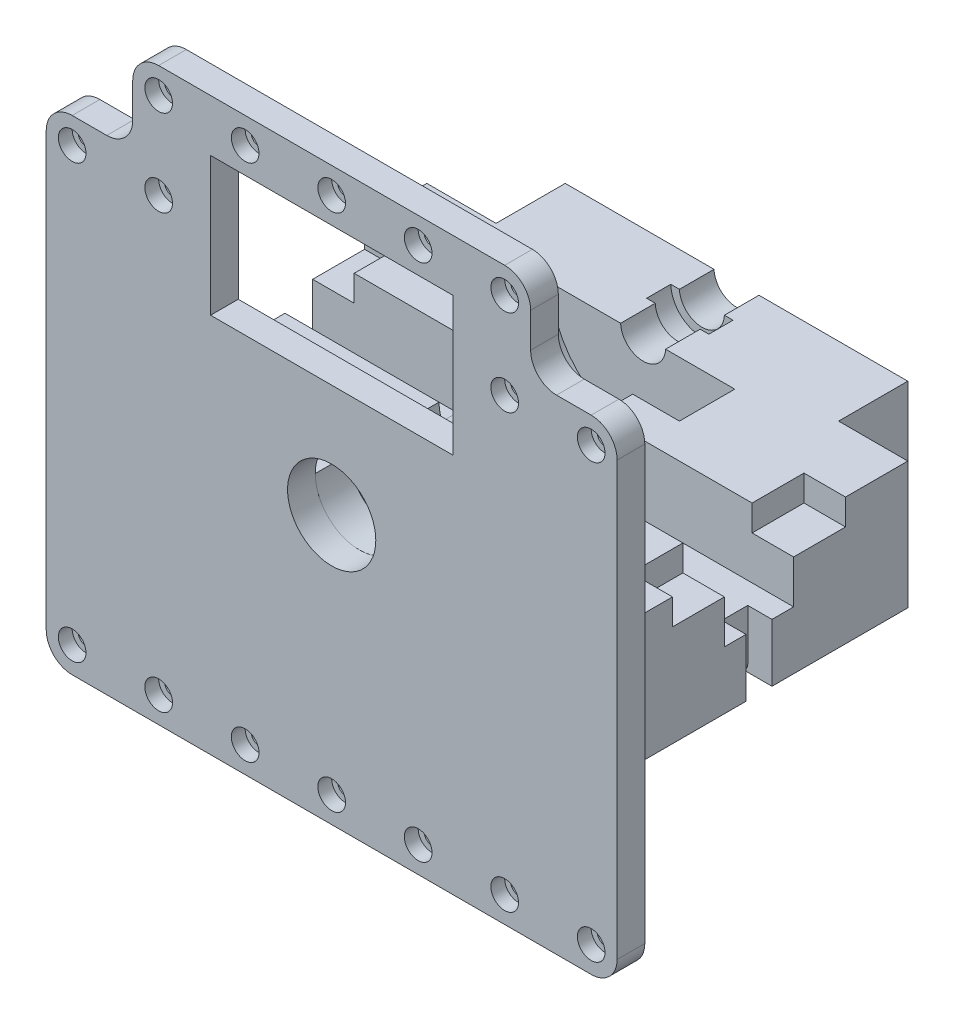
SolidWorks part; units mm, degrees
ref_plane "Front Plane" through (0, 0, 0) normal (0, 0, 1) x (1, 0, 0)
ref_plane "Top Plane" through (0, 0, 0) normal (0, 1, 0) x (1, 0, 0)
ref_plane "Right Plane" through (0, 0, 0) normal (1, 0, 0) x (0, 0, -1)
sketch "Sketch2" plane through (0, 0, 0) normal (0, 0, 1) x (1, 0, 0)
  line L5 (-57.5, 60) -> (-57.5, 50)
  line L6 (-75, -97.5) -> (75, -97.5)
  line L24 (-82.5, -90) -> (-82.5, 35)
  line L25 (-50, 67.5) -> (50, 67.5)
  line L26 (82.5, -90) -> (82.5, 35)
  line L27 (0, -100) -> (0, 100) construction
  line L28 (-100, 0) -> (100, 0) construction
  line L29 (-65, 42.5) -> (-75, 42.5)
  line L34 (57.5, 60) -> (57.5, 50)
  line L35 (65, 42.5) -> (75, 42.5)
  arc A12 (-82.5, 35) -> (-75, 42.5) centre (-75, 35) cw
  arc A19 (82.5, 35) -> (75, 42.5) centre (75, 35) ccw
  arc A20 (65, 42.5) -> (57.5, 50) centre (65, 50) cw
  arc A21 (57.5, 60) -> (50, 67.5) centre (50, 60) ccw
  arc A22 (-50, 67.5) -> (-57.5, 60) centre (-50, 60) ccw
  arc A23 (-65, 42.5) -> (-57.5, 50) centre (-65, 50) ccw
  arc A24 (-82.5, -90) -> (-75, -97.5) centre (-75, -90) ccw
  arc A25 (82.5, -90) -> (75, -97.5) centre (75, -90) cw
  point P0 (0, 0)
  point P39 (-57.5, 67.5)
  dimension "D5" = 25
  dimension "D6" = 82.5
  dimension "D7" = 7.5
  dimension "D2" = 25
  dimension "D3" = 165
  dimension "D8" = 7.5
  dimension "D1" = 67.5
  dimension "D4" = 82.5
extrude "Boss-Extrude1" add sketch "Sketch2" against normal blind 8
sketch "Sketch3" plane through (0, 0, 0) normal (0, 0, 1) x (1, 0, 0)
  line L0 (0, 100) -> (0, -100) construction
  circle A0 centre (0, -20) radius 12.75
  dimension "D1" = 25.5
  dimension "D2" = 20
extrude "Cut-Extrude1" cut sketch "Sketch3" against normal up to surface (8 mm away) up to face at (0, 13.75, -8)
sketch "Sketch5" plane through (0, 0, -8) normal (0, 0, -1) x (-1, 0, 0)
  line L3 (-69.5, -87) -> (-69.5, -20)
  line L4 (0, 67.5) -> (0, -97.5) construction
  line L5 (-82.5, -90) -> (-82.5, 35) construction
  line L6 (-69.5, -20) -> (69.5, -20)
  line L7 (-69.5, -87) -> (69.5, -87)
  line L8 (75, -97.5) -> (-75, -97.5) construction
  line L9 (69.5, -87) -> (69.5, -20)
  line L10 (-50, 67.5) -> (50, 67.5) construction
  point P10 (0, -87)
  point P11 (0, -20)
  dimension "D1" = 10.5
  dimension "D2" = 67
  dimension "D3" = 13
extrude "Boss-Extrude2" add sketch "Sketch5" along normal blind 109
sketch "Sketch6" plane through (0, 0, -8) normal (0, 0, -1) x (-1, 0, 0)
  circle A0 centre (0, -20) radius 26.5
  circle A1 centre (0, -20) radius 12.75 construction
  dimension "D1" = 53
extrude "Cut-Extrude2" cut sketch "Sketch6" along normal blind 16 from offset 10
sketch "Sketch7" plane through (0, 0, -8) normal (0, 0, -1) x (-1, 0, 0)
  circle A0 centre (0, -20) radius 6.5
  circle A1 centre (0, -20) radius 12.75 construction
  dimension "D1" = 13
extrude "Cut-Extrude3" cut sketch "Sketch7" along normal up to surface (109 mm away) up to face at (0, -53.5, -117)
sketch "Sketch10" plane through (0, 0, -8) normal (0, 0, -1) x (-1, 0, 0)
  line L0 (-69.5, -20) -> (-69.5, -20.25)
  line L1 (-69.5, -20) -> (-69.5, -87) construction
  line L2 (-69.5, -20.25) -> (69.5, -20.25)
  line L3 (69.5, -87) -> (69.5, -20) construction
  line L4 (69.5, -20.25) -> (69.5, -20)
  line L5 (69.5, -20) -> (-69.5, -20)
  dimension "D1" = 0.25
extrude "Cut-Extrude4" cut sketch "Sketch10" along normal up to surface (109 mm away) up to face at (0, -43.4167, -117)
sketch "Sketch11" plane through (0, 0, -8) normal (0, 0, -1) x (-1, 0, 0)
  line L0 (-69.5, -72) -> (-54.5, -72)
  line L1 (-69.5, -20.25) -> (-69.5, -87) construction
  line L2 (-54.5, -72) -> (-54.5, -87)
  line L3 (-69.5, -87) -> (69.5, -87) construction
  line L4 (-69.5, -72) -> (-69.5, -87)
  line L5 (-69.5, -87) -> (-54.5, -87)
  line L11 (0, 87.7767) -> (0, -101.3295) construction
  line L12 (69.5, -87) -> (54.5, -87)
  line L13 (69.5, -72) -> (69.5, -87)
  line L14 (54.5, -72) -> (54.5, -87)
  line L15 (69.5, -72) -> (54.5, -72)
  dimension "D1" = 15
  dimension "D2" = 15
sketch "Sketch14" plane through (69.5, 0, 0) normal (1, 0, 0) x (0, 0, -1)
  line L0 (44, 4.6823) -> (44, -72.994) construction
  line L2 (64, 4.6823) -> (64, -72.994) construction
  line L3 (8, -90) -> (8, 35) construction
  line L4 (74, 4.6823) -> (74, -72.994) construction
  line L5 (90, 4.6823) -> (90, -72.994) construction
  line L6 (100, 4.6823) -> (100, -72.994) construction
  dimension "D1" = 36
  dimension "D2" = 20
  dimension "D3" = 10
  dimension "D4" = 16
  dimension "D5" = 10
sketch "Sketch15" plane through (0, 0, -8) normal (0, 0, -1) x (-1, 0, 0)
  circle A0 centre (0, -20) radius 32.5
  circle A1 centre (0, -20) radius 12.75 construction
  dimension "D1" = 65
extrude "Cut-Extrude8" cut sketch "Sketch15" along normal blind 20 from offset 36
sketch "Sketch16" plane through (69.5, 0, 0) normal (1, 0, 0) x (0, 0, -1)
  line L0 (44, -20.25) -> (44, -40.25)
  line L1 (44, 4.6823) -> (44, -72.994) construction
  line L2 (44, -40.25) -> (64, -40.25)
  line L3 (64, 4.6823) -> (64, -72.994) construction
  line L4 (64, -40.25) -> (64, -20.25)
  line L5 (64, -20.25) -> (44, -20.25)
  dimension "D1" = 20
extrude "Cut-Extrude9" cut sketch "Sketch16" against normal through all both and the other way through all
sketch "Sketch17" plane through (0, 0, -8) normal (0, 0, -1) x (-1, 0, 0)
  circle A0 centre (0, -20) radius 26.5
  circle A1 centre (0, -20) radius 12.75 construction
  dimension "D1" = 53
extrude "Cut-Extrude10" cut sketch "Sketch17" along normal blind 26 from surface
sketch "Sketch20" plane through (0, 0, -8) normal (0, 0, -1) x (-1, 0, 0)
  line L0 (-69.5, -20.25) -> (-69.5, -87)
  line L1 (-69.5, -87) -> (69.5, -87)
  line L2 (69.5, -87) -> (69.5, -20.25)
  line L3 (69.5, -20.25) -> (-69.5, -20.25)
  line L4 (-69.5, -20.25) -> (-6.4952, -20.25) construction
  line L5 (-69.5, 4.6823) -> (-69.5, -72.994) construction
  line L6 (69.5, -87) -> (69.5, -20.25) construction
  line L7 (-69.5, -87) -> (69.5, -87) construction
extrude "Boss-Extrude6" add sketch "Sketch20" along normal blind 10 from surface at 56 starting at face at (0, -35.0625, -64)
sketch "Sketch21" plane through (0, 0, -8) normal (0, 0, -1) x (-1, 0, 0)
  circle A0 centre (0, -20) radius 13
  circle A1 centre (0, -20) radius 12.75 construction
  dimension "D1" = 26
extrude "Cut-Extrude12" cut sketch "Sketch21" along normal up to surface (66 mm away) up to face at (0, -33.375, -74)
fillet "Fillet1" radius 5 1 edges at (25.4202, -40.25, -54)
fillet "Fillet2" radius 5 1 edges at (-25.4202, -40.25, -54)
sketch "Sketch22" plane through (0, 0, -8) normal (0, 0, -1) x (-1, 0, 0)
  circle A0 centre (0, -20) radius 9
  circle A1 centre (0, -20) radius 12.75 construction
  dimension "D1" = 18
extrude "Cut-Extrude13" cut sketch "Sketch22" against normal blind 17 and the other way through all from surface at 109 starting at face at (0, -43.5417, -117)
sketch "Sketch23" plane through (0, 0, -117) normal (0, 0, -1) x (-1, 0, 0)
  line L0 (-8.9965, -20.25) -> (-6.4952, -20.25)
  line L1 (6.4952, -20.25) -> (8.9965, -20.25)
  arc A0 (-8.9965, -20.25) -> (8.9965, -20.25) centre (0, -20) ccw
  arc A1 (-6.4952, -20.25) -> (6.4952, -20.25) centre (0, -20) ccw
  arc A2 (-6.4952, -20.25) -> (6.4952, -20.25) centre (0, -20) ccw construction
  arc A3 (-8.9965, -20.25) -> (8.9965, -20.25) centre (0, -20) ccw construction
extrude "Boss-Extrude7" add sketch "Sketch23" against normal blind 10
sketch "Sketch24" plane through (0, 0, -117) normal (0, 0, -1) x (-1, 0, 0)
  line L0 (-69.5, -57) -> (-69.5, -87)
  line L1 (-69.5, 4.6823) -> (-69.5, -72.994) construction
  line L2 (-69.5, -87) -> (-39.5, -87)
  line L3 (-69.5, -87) -> (69.5, -87) construction
  line L4 (-39.5, -87) -> (-39.5, -57)
  line L5 (-39.5, -57) -> (-69.5, -57)
  line L6 (0, 119.6824) -> (0, -123.2201) construction
  line L7 (39.5, -57) -> (69.5, -57)
  line L8 (39.5, -87) -> (39.5, -57)
  line L9 (69.5, -87) -> (39.5, -87)
  line L10 (69.5, -57) -> (69.5, -87)
  dimension "D1" = 30
  dimension "D2" = 30
extrude "Cut-Extrude14" cut sketch "Sketch24" against normal up to surface (109 mm away) up to face at (0, -44.625, -8)
sketch "Sketch25" plane through (39.5, 0, 0) normal (1, 0, 0) x (0, 0, -1)
  line L0 (8, -57) -> (8, -87)
  line L1 (8, -87) -> (38, -87)
  line L2 (8, -87) -> (117, -87) construction
  line L3 (38, -87) -> (38, -57)
  line L4 (8, -57) -> (117, -57) construction
  line L5 (38, -57) -> (8, -57)
  line L6 (74, -57) -> (74, -87)
  line L7 (74, 4.6823) -> (74, -72.994) construction
  line L8 (74, -87) -> (117, -87)
  line L9 (117, -87) -> (117, -57)
  line L10 (117, -57) -> (74, -57)
  dimension "D1" = 30
extrude "Cut-Extrude15" cut sketch "Sketch25" against normal through all both and the other way through all
sketch "Sketch29" plane through (69.5, 0, 0) normal (1, 0, 0) x (0, 0, -1)
  line L0 (44, -20.25) -> (44, -27.75)
  line L1 (44, -40.25) -> (44, -20.25) construction
  line L2 (44, -27.75) -> (29, -27.75)
  line L3 (29, -27.75) -> (29, -20.25)
  line L4 (44, -20.25) -> (8, -20.25) construction
  line L5 (29, -20.25) -> (44, -20.25)
  line L6 (64, -20.25) -> (64, -27.75)
  line L7 (64, -20.25) -> (64, -40.25) construction
  line L8 (64, -27.75) -> (79, -27.75)
  line L9 (79, -27.75) -> (79, -20.25)
  line L10 (117, -20.25) -> (64, -20.25) construction
  line L11 (79, -20.25) -> (64, -20.25)
  dimension "D1" = 15
  dimension "D2" = 7.5
  dimension "D3" = 15
  dimension "D4" = 7.5
extrude "Cut-Extrude16" cut sketch "Sketch29" against normal blind 12 and the other way through all
sketch "Sketch30" plane through (-69.5, 0, 0) normal (-1, 0, 0) x (0, 0, 1)
  line L0 (-44, -20.25) -> (-29, -20.25)
  line L1 (-44, -20.25) -> (-8, -20.25) construction
  line L2 (-29, -20.25) -> (-29, -27.75)
  line L3 (-29, -27.75) -> (-44, -27.75)
  line L4 (-44, -20.25) -> (-44, -40.25) construction
  line L5 (-44, -27.75) -> (-44, -20.25)
  line L6 (-64, -27.75) -> (-79, -27.75)
  line L7 (-64, -40.25) -> (-64, -20.25) construction
  line L8 (-79, -27.75) -> (-79, -20.25)
  line L9 (-117, -20.25) -> (-64, -20.25) construction
  line L10 (-79, -20.25) -> (-64, -20.25)
  line L11 (-64, -20.25) -> (-64, -27.75)
  dimension "D1" = 15
  dimension "D2" = 15
  dimension "D3" = 7.5
extrude "Cut-Extrude17" cut sketch "Sketch30" against normal blind 12
sketch "Sketch31" plane through (-69.5, 0, 0) normal (-1, 0, 0) x (0, 0, 1)
  line L7 (-57.75, -40.25) -> (-50.25, -40.25)
  line L9 (-44, -40.25) -> (-64, -40.25) construction
  line L11 (-50.25, -40.25) -> (-50.25, -57)
  line L12 (-8, -57) -> (-117, -57) construction
  line L13 (-50.25, -57) -> (-57.75, -57)
  line L14 (-57.75, -57) -> (-57.75, -40.25)
  line L15 (-57.75, -30.25) -> (-57.75, -40.25) construction
  line L16 (-50.25, -40.25) -> (-50.25, -30.25) construction
extrude "Cut-Extrude18" cut sketch "Sketch31" against normal blind 7
sketch "Sketch32" plane through (69.5, 0, 0) normal (1, 0, 0) x (0, 0, -1)
  line L0 (50.25, -40.25) -> (57.75, -40.25)
  line L1 (57.75, -40.25) -> (57.75, -57)
  line L2 (8, -57) -> (117, -57) construction
  line L3 (57.75, -57) -> (50.25, -57)
  line L4 (50.25, -57) -> (50.25, -40.25)
  line L5 (64, -40.25) -> (44, -40.25) construction
  line L6 (50.25, -30.25) -> (50.25, -40.25) construction
  line L7 (57.75, -40.25) -> (57.75, -30.25) construction
  dimension "D1" = 7.5
extrude "Cut-Extrude19" cut sketch "Sketch32" against normal blind 7
sketch "Sketch38" plane through (0, -20.25, 0) normal (0, 1, 0) x (1, 0, 0)
  line L0 (49.5, 117) -> (49.5, 97)
  line L1 (69.5, 117) -> (6.4952, 117) construction
  line L2 (49.5, 97) -> (69.5, 97)
  line L3 (69.5, 117) -> (69.5, 79) construction
  line L4 (69.5, 97) -> (69.5, 117)
  line L5 (69.5, 117) -> (49.5, 117)
  line L6 (-69.5, 117) -> (-49.5, 117)
  line L7 (-6.4952, 117) -> (-69.5, 117) construction
  line L8 (-49.5, 117) -> (-49.5, 97)
  line L10 (-49.5, 97) -> (-69.5, 97)
  line L11 (-69.5, 117) -> (-69.5, 79) construction
  line L12 (-69.5, 97) -> (-69.5, 117)
  dimension "D1" = 20
  dimension "D2" = 20
  dimension "D3" = 20
  dimension "D4" = 20
extrude "Cut-Extrude20" cut sketch "Sketch38" against normal through all
fillet "Fillet3" radius 2 1 edges at (62.5, -57, -54)
fillet "Fillet4" radius 2 1 edges at (-62.5, -57, -54)
sketch "Sketch39" plane through (0, 0, -74) normal (0, 0, -1) x (-1, 0, 0)
  line L0 (-39.5, -81.5) -> (-39.5, -87)
  line L1 (-39.5, -87) -> (-39.5, -57) construction
  line L2 (-39.5, -87) -> (39.5, -87)
  line L3 (39.5, -87) -> (39.5, -81.5)
  line L4 (39.5, -57) -> (39.5, -87) construction
  line L5 (39.5, -81.5) -> (-39.5, -81.5)
  line L6 (72.5, -82.5) -> (-72.5, -82.5) construction
  dimension "D1" = 1
extrude "Cut-Extrude21" cut sketch "Sketch39" against normal up to surface (36 mm away) up to face at (0, -72, -38)
sketch "Sketch41" plane through (0, 0, 0) normal (0, 0, 1) x (1, 0, 0)
  point P0 (-75, 35)
  point P3 (-50, 35)
  point P6 (-50, 60)
  point P9 (-25, 60)
  point P12 (0, 60)
  point P15 (25, 60)
  point P18 (50, 60)
  point P21 (50, 35)
  point P24 (75, 35)
  point P28 (-75, -90)
  point P31 (-50, -90)
  point P34 (-25, -90)
  point P37 (0, -90)
  point P40 (25, -90)
  point P43 (50, -90)
  point P46 (75, -90)
hole_wizard "CBORE for M4 SHCS1" positions "Sketch41" profile "Sketch42" counterbore size "M4" standard "ANSI Metric" end condition through all
sketch "Sketch42" plane through (-75, 35, 0) normal (1, 0, 0) x (0, -1, 0)
  line L0 (0, 0) -> (0, 117)
  line L1 (0, 117) -> (2.25, 117)
  line L3 (2.25, 117) -> (2.25, 4)
  line L4 (2.25, 4) -> (4, 4)
  line L5 (4, 4) -> (4, 0)
  line L7 (4, 0) -> (0, 0)
  line L11 (0, -6.35) -> (0, 107.95) construction
  dimension "Thru Hole Dia." = 4.5
  dimension "Thru Hole Depth" = 117
  dimension "C'Bore Dia." = 8
  dimension "C'Bore Depth" = 4
sketch "Sketch43" plane through (0, 0, 0) normal (0, 0, 1) x (1, 0, 0)
  line L0 (-35, 52.5) -> (35, 52.5)
  line L1 (35, 52.5) -> (35, 12.5)
  line L2 (35, 12.5) -> (-35, 12.5)
  line L3 (-35, 12.5) -> (-35, 52.5)
  line L4 (50, 67.5) -> (-50, 67.5) construction
  line L6 (82.5, -90) -> (82.5, 35) construction
  dimension "D1" = 15
  dimension "D2" = 70
  dimension "D3" = 47.5
  dimension "D4" = 40
extrude "Cut-Extrude22" cut sketch "Sketch43" against normal through all both and the other way through all
